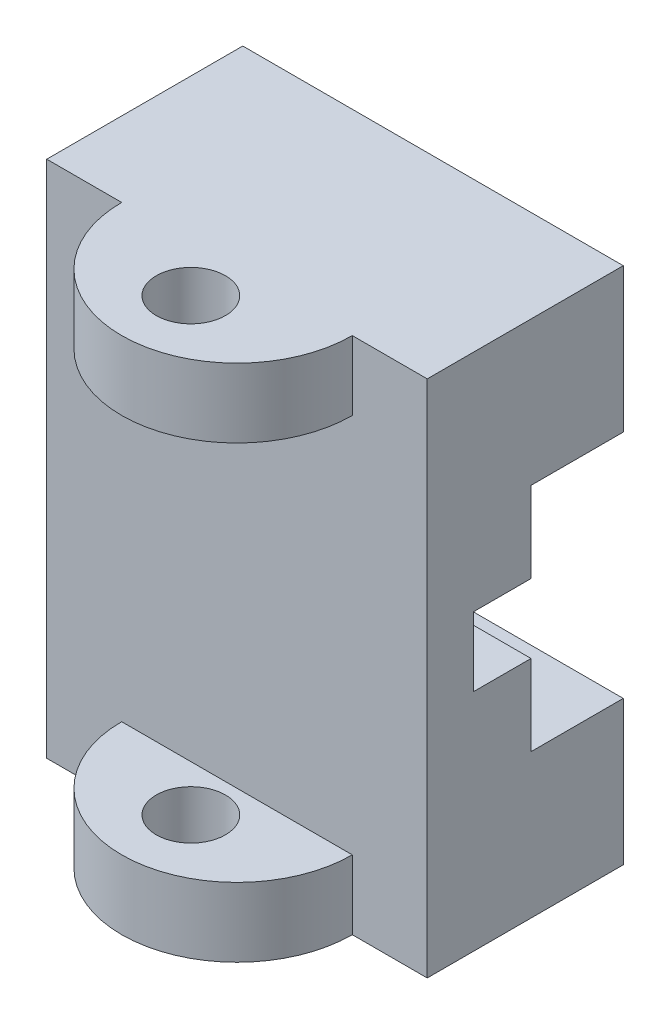
SolidWorks part; units mm, degrees
ref_plane "Спереди" through (0, 0, 0) normal (0, 0, 1) x (1, 0, 0)
ref_plane "Сверху" through (0, 0, 0) normal (0, 1, 0) x (1, 0, 0)
ref_plane "Справа" through (0, 0, 0) normal (1, 0, 0) x (0, 0, -1)
sketch "Эскиз1" plane through (0, 0, 0) normal (0, 0, 1) x (1, 0, 0)
  line L1 (16.5, -22.5) -> (-16.5, -22.5)
  line L2 (16.5, -22.5) -> (16.5, 22.5)
  line L3 (16.5, 22.5) -> (-16.5, 22.5)
  line L4 (-16.5, -22.5) -> (-16.5, 22.5)
  line L5 (16.5, -22.5) -> (-16.5, 22.5) construction
  line L6 (16.5, 22.5) -> (-16.5, -22.5) construction
  point P0 (0, 0)
  dimension "D1" = 33
  dimension "D2" = 45
extrude "Бобышка-Вытянуть1" add sketch "Эскиз1" along normal blind 17
sketch "Эскиз2" plane through (-16.5, 0, 0) normal (-1, 0, 0) x (0, 0, 1)
  line L0 (17, 0) -> (0, 0) construction
  line L1 (17, 22.5) -> (17, -22.5) construction
  line L2 (0, 22.5) -> (0, -22.5) construction
  line L3 (8, 10) -> (0, 10)
  line L4 (8, 10) -> (8, -10)
  line L5 (8, -10) -> (0, -10)
  line L6 (0, 10) -> (0, -10)
  line L7 (8, 10) -> (0, -10) construction
  line L8 (8, -10) -> (0, 10) construction
  line L10 (13, 3) -> (8, 3)
  line L11 (13, 3) -> (13, -3)
  line L12 (13, -3) -> (8, -3)
  line L13 (8, 3) -> (8, -3)
  line L14 (13, 3) -> (8, -3) construction
  line L15 (13, -3) -> (8, 3) construction
  point P5 (4, 0)
  point P12 (10.5, 0)
  line M1 (0, 22.5) -> (0, -22.5)
  dimension "D1" = 8
  dimension "D2" = 20
  dimension "D3" = 6
  dimension "D4" = 5
extrude "Вырез-Вытянуть1" cut sketch "Эскиз2" against normal through all contours L5 L4 L3 M1 | L12 L11 L10 L4
sketch "Эскиз4" plane through (0, -22.5, 0) normal (0, -1, 0) x (1, 0, 0)
  line L0 (-16.5, 17) -> (16.5, 17) construction
  line L1 (-10, 17) -> (10, 17)
  arc A0 (-10, 17) -> (10, 17) centre (0, 17) cw
  circle A1 centre (0, 21) radius 3
  dimension "D1" = 10
  dimension "D2" = 6
  dimension "D3" = 4
extrude "Бобышка-Вытянуть2" add sketch "Эскиз4" against normal blind 6
mirror "Зеркальное отражение1" about plane through (0, 0, 0) normal (0, 1, 0) of "Бобышка-Вытянуть2"
